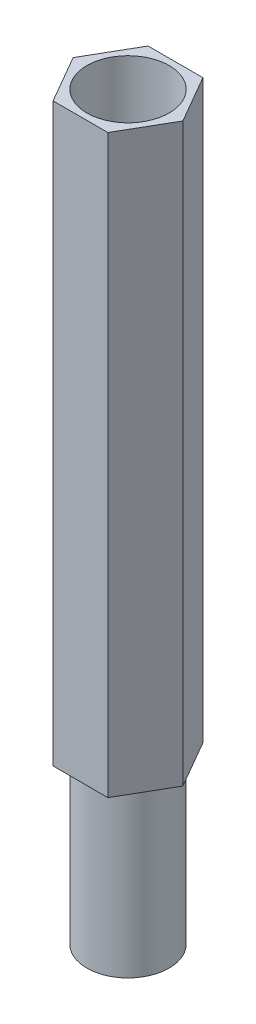
SolidWorks part; units mm, degrees
ref_plane "前视基准面" through (0, 0, 0) normal (0, 0, 1) x (1, 0, 0)
ref_plane "上视基准面" through (0, 0, 0) normal (0, 1, 0) x (1, 0, 0)
ref_plane "右视基准面" through (0, 0, 0) normal (1, 0, 0) x (0, 0, -1)
other "Configuration Table"
ref_plane "基准面1" through (0, 0, 0) normal (0, -1, 0) x (1, 0, 0)
sketch "草图1" plane through (0, 0, 0) normal (0, -1, 0) x (1, 0, 0)
  line L0 (-1, 1.7321) -> (-2, 0)
  line L1 (-2, 0) -> (-1, -1.7321)
  line L2 (-1, -1.7321) -> (1, -1.7321)
  line L3 (1, -1.7321) -> (2, 0)
  line L4 (2, 0) -> (1, 1.7321)
  line L5 (1, 1.7321) -> (-1, 1.7321)
  dimension "D1" = 1
  dimension "D2" = 3
  dimension "D3" = 4
  dimension "D4" = 1.7321
  dimension "D5" = 3.4641
extrude "凸台-拉伸1" add sketch "草图1" against normal blind 21
sketch "草图2" plane through (0, 0, 0) normal (0, 0, 1) x (1, 0, 0)
  line L0 (1.5, 0) -> (0, 0)
  line L1 (0, 0) -> (0, -6)
  line L2 (0, -6) -> (1.5, -6)
  line L3 (1.5, -6) -> (1.5, 0)
  line L4 (0, 0) -> (0, -6) construction
  dimension "D1" = 1.5
  dimension "D2" = 6
revolve "旋转1" add sketch "草图2" angle 360 about L4
hole_wizard "Ø3.0 (3) 直径孔1" positions "草图4" profile "草图3" hole size "Ø3.0" standard "ANSI Metric"
sketch "草图4" plane through (0, 21, 0) normal (0, 1, 0) x (1, 0, 0)
  point P0 (0, 0)
sketch "草图3" plane through (0, 21, 0) normal (1, 0, 0) x (0, 0, 1)
  line L0 (0, 0) -> (0, 5)
  line L1 (0, 5) -> (1.5, 5)
  line L2 (1.5, 5) -> (1.5, 0)
  line L5 (1.5, 0) -> (0, 0)
  line L10 (0, 5) -> (-1.5, 5) construction
  line L11 (0, -6.35) -> (0, 107.95) construction
  dimension "孔直径" = 3
  dimension "孔深度" = 5
  dimension "导头角度" = 180
